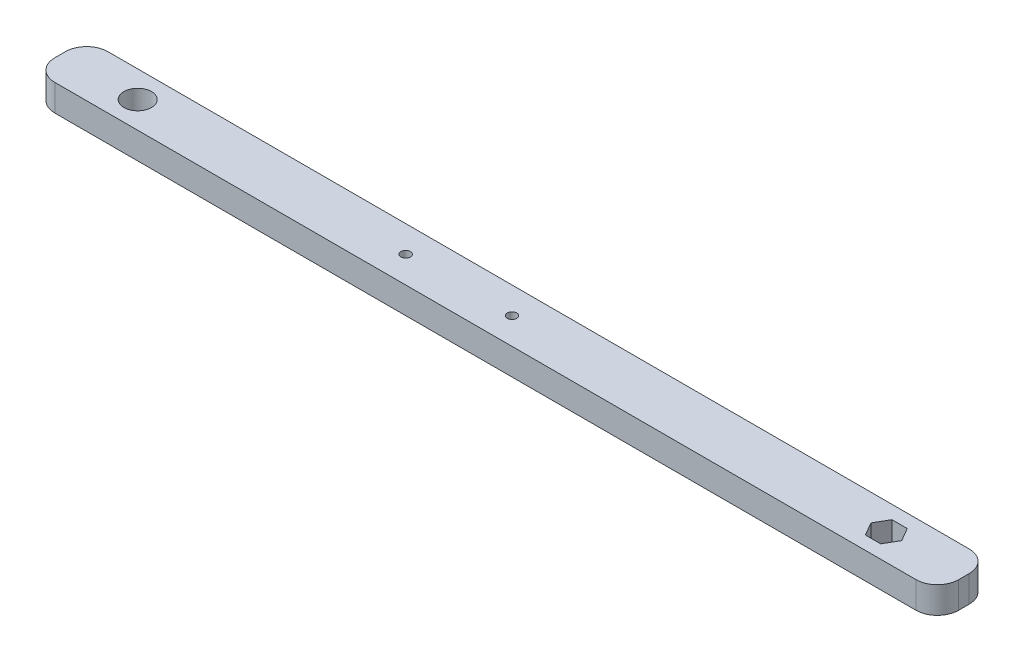
SolidWorks part; units mm, degrees
material "Acrylic (Medium-high impact)"
ref_plane "Front Plane" through (0, 0, 0) normal (0, 0, 1) x (1, 0, 0)
ref_plane "Top Plane" through (0, 0, 0) normal (0, 1, 0) x (1, 0, 0)
ref_plane "Right Plane" through (0, 0, 0) normal (1, 0, 0) x (0, 0, -1)
sketch "Sketch1" plane through (0, 0, 0) normal (0, 1, 0) x (1, 0, 0)
  line L0 (18.542, 6.35) -> (197.358, 6.35) construction
  line L1 (0, 0) -> (215.9, 0)
  line L2 (0, 0) -> (0, 12.7)
  line L3 (0, 12.7) -> (215.9, 12.7)
  line L4 (215.9, 0) -> (215.9, 12.7)
  line L6 (24.0999, 6.35) -> (21.321, 11.1633) construction
  line L7 (21.321, 11.1633) -> (15.763, 11.1633) construction
  line L8 (15.763, 11.1633) -> (12.9841, 6.35) construction
  line L9 (12.9841, 6.35) -> (15.763, 1.5367) construction
  line L10 (15.763, 1.5367) -> (21.321, 1.5367) construction
  line L11 (21.321, 1.5367) -> (24.0999, 6.35) construction
  line L12 (199.1911, 9.525) -> (195.5249, 9.525)
  line L13 (195.5249, 9.525) -> (193.6918, 6.35)
  line L14 (193.6918, 6.35) -> (195.5249, 3.175)
  line L15 (195.5249, 3.175) -> (199.1911, 3.175)
  line L16 (199.1911, 3.175) -> (201.0242, 6.35)
  line L17 (201.0242, 6.35) -> (199.1911, 9.525)
  circle A0 centre (18.542, 6.35) radius 4.8133 construction
  circle A1 centre (197.358, 6.35) radius 4.8133 construction
  circle A2 centre (18.542, 6.35) radius 4.8133 construction
  circle A3 centre (197.358, 6.35) radius 3.175 construction
  circle A4 centre (18.542, 6.35) radius 3.302
  point P9 (107.95, 6.35)
  point P10 (107.95, 12.7)
  point P12 (215.9, 6.35)
  dimension "D2" = 9.6266
  dimension "D5" = 9.6266
  dimension "D6" = 6.35
  dimension "D7" = 6.604
  dimension "D1" = 215.9
  dimension "D3" = 178.816
  dimension "D4" = 12.7
extrude "Boss-Extrude1" add sketch "Sketch1" along normal blind 6.35
fillet "Fillet1" radius 5.08 4 edges at (215.9, 3.175, -12.7) (215.9, 3.175, 0) (0, 3.175, -12.7) (0, 3.175, 0)
sketch "Sketch4" plane through (0, 6.35, 0) normal (0, 1, 0) x (1, 0, 0)
  line L1 (215.9, 5.08) -> (215.9, 7.62) construction
  line L2 (210.82, 12.7) -> (5.08, 12.7) construction
  circle A0 centre (107.95, 6.35) radius 1.1303
  circle A1 centre (82.55, 6.35) radius 1.1303
  point P5 (215.9, 6.35)
  point P8 (107.95, 12.7)
  dimension "D1" = 2.2606
  dimension "D2" = 25.4
extrude "Cut-Extrude1" cut sketch "Sketch4" against normal blind 21.59
